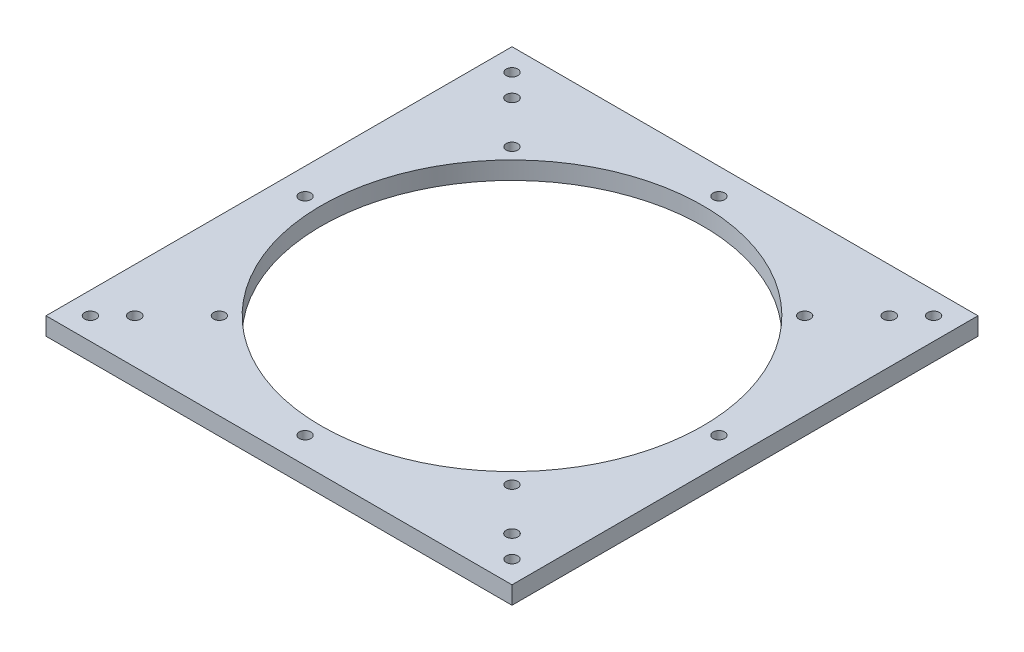
SolidWorks part; units mm, degrees
ref_plane "前视基准面" through (0, 0, 0) normal (0, 0, 1) x (1, 0, 0)
ref_plane "上视基准面" through (0, 0, 0) normal (0, 1, 0) x (1, 0, 0)
ref_plane "右视基准面" through (0, 0, 0) normal (1, 0, 0) x (0, 0, -1)
other "Configuration Table"
sketch "草图1" plane through (0, 0, 0) normal (0, 1, 0) x (1, 0, 0)
  line L0 (0, 101) -> (0, 85.5)
  line L2 (-105, -105) -> (105, -105)
  line L3 (-105, -105) -> (-105, 105)
  line L4 (-105, 105) -> (105, 105)
  line L5 (105, -105) -> (105, 105)
  line L6 (-105, -105) -> (105, 105) construction
  line L7 (-105, 105) -> (105, -105) construction
  circle A0 centre (0, 0) radius 72.5
  circle A1 centre (0, 0) radius 85.5
  circle A2 centre (0, 0) radius 101
  circle A3 centre (0, 93.25) radius 2.6
  circle A4 centre (93.25, 0) radius 2.6
  circle A5 centre (0, -93.25) radius 2.6
  circle A6 centre (-93.25, 0) radius 2.6
  point P19 (0, 0)
  dimension "D1" = 145
  dimension "D3" = 202
  dimension "D4" = 5.2
  dimension "D6" = 210
  dimension "D7" = 210
  dimension "D2" = 13
  dimension "D5" = 4
extrude "凸台-拉伸1" add sketch "草图1" along normal blind 8
sketch "草图2" plane through (0, 8, 0) normal (0, 1, 0) x (1, 0, 0)
  line L0 (-105, 155) -> (-55, 155)
  line L1 (-105, 105) -> (-95, 105)
  line L2 (-105, 105) -> (-105, 95)
  line L3 (-105, 95) -> (-95, 95)
  line L4 (-95, 105) -> (-95, 95)
  line L5 (-105, 105) -> (105, 105)
  line L6 (-105, 105) -> (-105, 155)
  line L7 (-105, 155) -> (105, 155)
  line L8 (105, 105) -> (105, 155)
  circle A0 centre (-95, 95) radius 2.6
  circle A1 centre (0, 93.25) radius 2.6
  circle A2 centre (95, 95) radius 2.6
  circle A3 centre (95, -95) radius 2.6
  circle A4 centre (-95, -95) radius 2.6
  circle A5 centre (65.9377, 65.9377) radius 2.6
  circle A6 centre (93.25, 0) radius 2.6
  circle A7 centre (65.9377, -65.9377) radius 2.6
  circle A8 centre (0, -93.25) radius 2.6
  circle A9 centre (-65.9377, -65.9377) radius 2.6
  circle A10 centre (-93.25, 0) radius 2.6
  circle A11 centre (-65.9377, 65.9377) radius 2.6
  point P17 (0, 0)
  point P33 (0, 0)
  dimension "D3" = 4
  dimension "D4" = 5.2
  dimension "D5" = 8
  dimension "D1" = 10
  dimension "D2" = 10
  dimension "D6" = 50
  dimension "D7" = 50
extrude "切除-拉伸1" cut sketch "草图2" against normal blind 10 contours A7 | A2 | A11 | A5 | A9 | A3 | A4 | A0
sketch "草图3" plane through (0, 8, 0) normal (0, 1, 0) x (1, 0, 0)
  circle A0 centre (0, 0) radius 86
  dimension "D1" = 172
extrude "切除-拉伸2" cut sketch "草图3" against normal blind 10
sketch "草图4" plane through (0, 8, 0) normal (0, 1, 0) x (1, 0, 0)
  line L1 (-105, 105) -> (-85, 105)
  line L2 (-105, 105) -> (-105, 85)
  line L3 (-105, 85) -> (-85, 85)
  line L4 (-85, 105) -> (-85, 85)
  circle A0 centre (-85, 85) radius 2.65
  circle A1 centre (85, 85) radius 2.65
  circle A2 centre (85, -85) radius 2.65
  circle A3 centre (-85, -85) radius 2.65
  point P6 (0, 0)
  point P15 (0, 0)
  dimension "D3" = 5.3
  dimension "D1" = 20
  dimension "D2" = 20
  dimension "D4" = 4
extrude "切除-拉伸3" cut sketch "草图4" against normal through all contours A1 | A3 | A0 | A2
